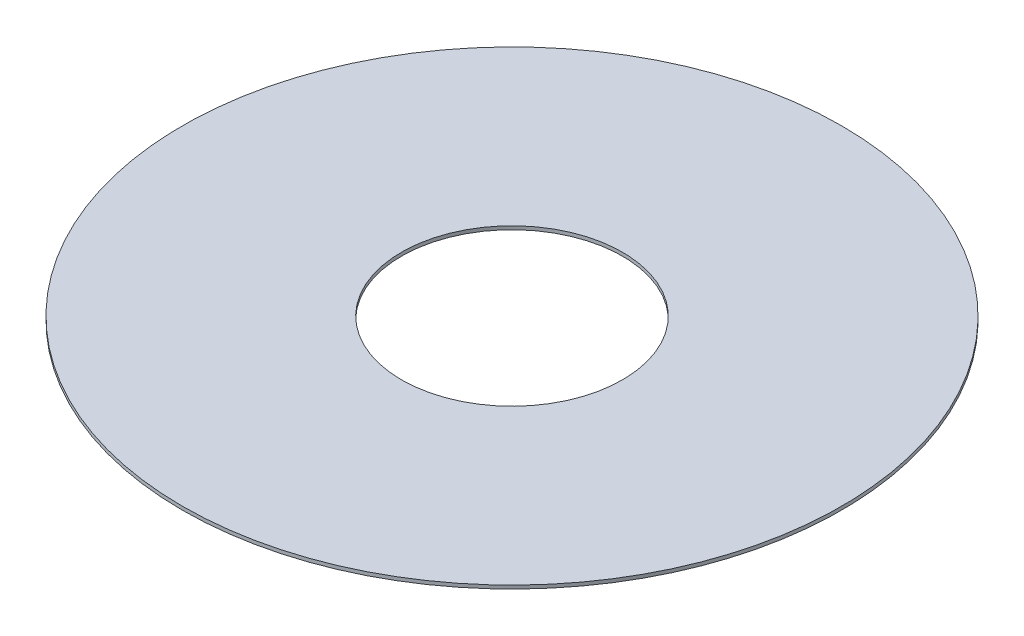
SolidWorks part; units mm, degrees
material "1060 Alloy"
ref_plane "Front Plane" through (0, 0, 0) normal (0, 0, 1) x (1, 0, 0)
ref_plane "Top Plane" through (0, 0, 0) normal (0, 1, 0) x (1, 0, 0)
ref_plane "Right Plane" through (0, 0, 0) normal (1, 0, 0) x (0, 0, -1)
sketch "Sketch1" plane through (0, 0, 0) normal (0, 1, 0) x (1, 0, 0)
  circle A0 centre (0, 0) radius 47.7
  circle A1 centre (0, 0) radius 16
  dimension "D1" = 32
  dimension "D2" = 95.4
extrude "Boss-Extrude1" add sketch "Sketch1" along normal blind 0.5
